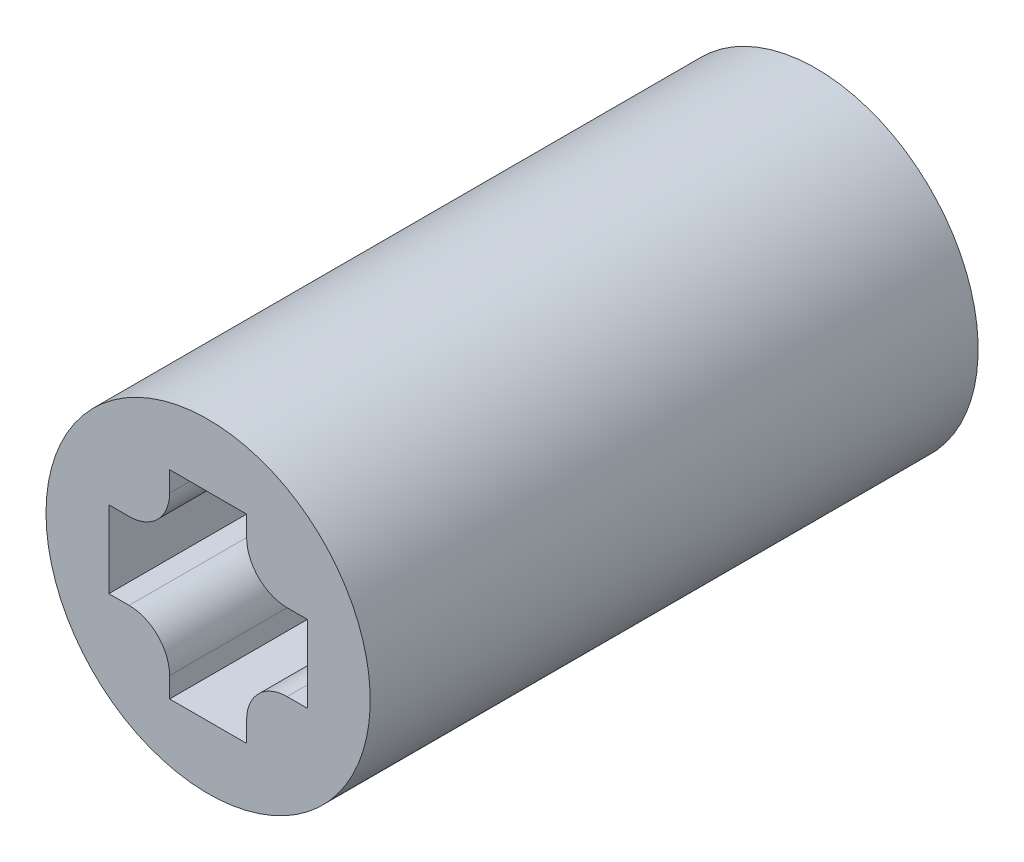
SolidWorks part; units mm, degrees
ref_plane "Front Plane" through (0, 0, 0) normal (0, 0, 1) x (1, 0, 0)
ref_plane "Top Plane" through (0, 0, 0) normal (0, 1, 0) x (1, 0, 0)
ref_plane "Right Plane" through (0, 0, 0) normal (1, 0, 0) x (0, 0, -1)
sketch "Sketch1" plane through (0, 0, 0) normal (0, 0, 1) x (1, 0, 0)
  circle A0 centre (0, 0) radius 4.5
  dimension "D1" = 9
extrude "Boss-Extrude1" add sketch "Sketch1" along normal blind 15
sketch "Sketch2" plane through (0, 0, 0) normal (0, 0, -1) x (-1, 0, 0)
  line L1 (-2, 3) -> (2, 3)
  line L2 (-2, 3) -> (-2, -3)
  line L3 (-2, -3) -> (2, -3)
  line L4 (2, 3) -> (2, -3)
  line L5 (-2, 3) -> (2, -3) construction
  line L6 (-2, -3) -> (2, 3) construction
  point P0 (0, 0)
  dimension "D1" = 4
  dimension "D2" = 6
extrude "Cut-Extrude1" cut sketch "Sketch2" against normal blind 7
sketch "Sketch3" plane through (0, 0, 15) normal (0, 0, 1) x (1, 0, 0)
  line L0 (-0.95, -0.95) -> (-0.95, -2.45)
  line L1 (-2.45, 0.95) -> (-0.95, 0.95)
  line L2 (-2.45, 0.95) -> (-2.45, -0.95)
  line L3 (-2.45, -0.95) -> (-0.95, -0.95)
  line L4 (2.45, 0.95) -> (2.45, -0.95)
  line L7 (-0.95, 2.45) -> (0.95, 2.45)
  line L8 (-0.95, 2.45) -> (-0.95, 0.95)
  line L9 (-0.95, -2.45) -> (0.95, -2.45)
  line L10 (0.95, 2.45) -> (0.95, 0.95)
  line L15 (0.95, 0.95) -> (2.45, 0.95)
  line L17 (0.95, -0.95) -> (0.95, -2.45)
  line L19 (0.95, -0.95) -> (2.45, -0.95)
  point P0 (0, 0)
  point P5 (0, 0)
  dimension "D1" = 4.9
  dimension "D2" = 1.9
  dimension "D3" = 4.9
  dimension "D4" = 1.9
extrude "Cut-Extrude2" cut sketch "Sketch3" against normal blind 7
fillet "Fillet3" radius 1 4 edges at (-0.95, -0.95, 11.5) (0.95, -0.95, 11.5) (-0.95, 0.95, 11.5) (0.95, 0.95, 11.5)
fillet "Fillet4" radius 0.9 4 edges at (2, -3, 3.5) (-2, -3, 3.5) (2, 3, 3.5) (-2, 3, 3.5)
sketch "Sketch4" plane through (0, 0, 0) normal (0, 0, -1) x (-1, 0, 0)
  circle A0 centre (0, 0) radius 4.5
  circle A1 centre (0, 0) radius 4
  dimension "D1" = 8
extrude "Cut-Extrude3" cut sketch "Sketch4" against normal blind 15
sketch "Sketch6" plane through (0, 0, 0) normal (0, 0, -1) x (-1, 0, 0)
  line L1 (-2.5, 3.5) -> (2.5, 3.5)
  line L2 (-2.5, 3.5) -> (-2.5, -3.5)
  line L3 (-2.5, -3.5) -> (2.5, -3.5)
  line L4 (2.5, 3.5) -> (2.5, -3.5)
  line L5 (-2.5, 3.5) -> (2.5, -3.5) construction
  line L6 (-2.5, -3.5) -> (2.5, 3.5) construction
  line L7 (-4.6645, 4.3419) -> (4.6645, 4.3419)
  line L8 (-4.6645, 4.3419) -> (-4.6645, -4.3419)
  line L9 (-4.6645, -4.3419) -> (4.6645, -4.3419)
  line L10 (4.6645, 4.3419) -> (4.6645, -4.3419)
  line L11 (-4.6645, 4.3419) -> (4.6645, -4.3419) construction
  line L12 (-4.6645, -4.3419) -> (4.6645, 4.3419) construction
  point P0 (0, 0)
  point P5 (0, 0)
  dimension "D1" = 7
  dimension "D2" = 5
extrude "Cut-Extrude4" cut sketch "Sketch6" against normal blind 7
sketch "Sketch7" plane through (0, 0, 15) normal (0, 0, 1) x (1, 0, 0)
  circle A0 centre (0, 0) radius 3.5
  circle A1 centre (0, 0) radius 4
  dimension "D1" = 7
extrude "Boss-Extrude2" add sketch "Sketch7" against normal blind 15
sketch "Sketch8" plane through (2.5, 0, 0) normal (1, 0, 0) x (0, 0, -1)
  line L1 (0, 2.4495) -> (-7.8, 2.4495)
  line L2 (0, 2.4495) -> (0, -2.4495)
  line L3 (0, -2.4495) -> (-7.8, -2.4495)
  line L4 (-7.8, 2.4495) -> (-7.8, -2.4495)
  dimension "D1" = 7.8
extrude "Boss-Extrude3" add sketch "Sketch8" along normal blind 1
sketch "Sketch9" plane through (-2.5, 0, 0) normal (-1, 0, 0) x (0, 0, 1)
  line L1 (0, 2.4495) -> (7.7, 2.4495)
  line L2 (0, 2.4495) -> (0, -2.5505)
  line L3 (0, -2.5505) -> (7.7, -2.5505)
  line L4 (7.7, 2.4495) -> (7.7, -2.5505)
  dimension "D1" = 7.7
  dimension "D2" = 5
extrude "Boss-Extrude4" add sketch "Sketch9" along normal blind 1
sketch "Sketch10" plane through (0, 0, 0) normal (0, 0, -1) x (-1, 0, 0)
  circle A0 centre (0, 0) radius 4
  circle A1 centre (0, 0) radius 4.4988
extrude "Cut-Extrude7" cut sketch "Sketch10" against normal blind 21 contours A1 | A0
